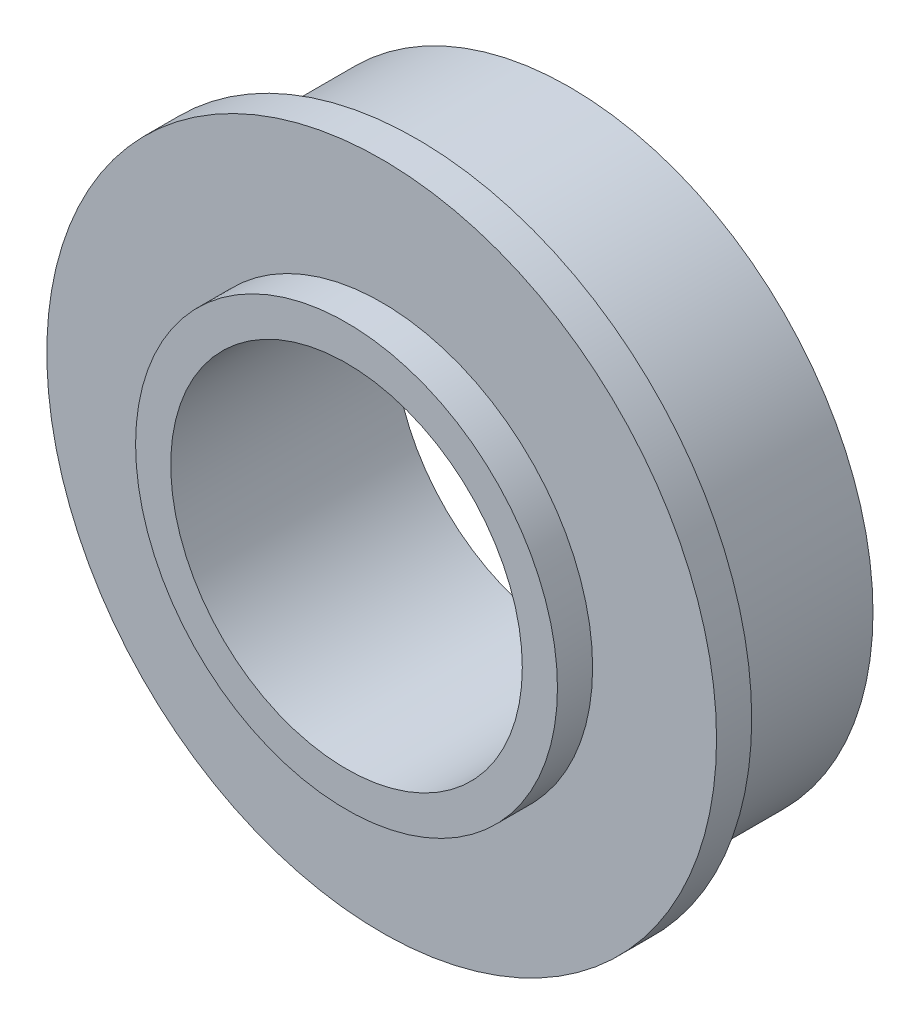
SolidWorks part; units mm, degrees
ref_plane "Front Plane" through (0, 0, 0) normal (0, 0, 1) x (1, 0, 0)
ref_plane "Top Plane" through (0, 0, 0) normal (0, 1, 0) x (1, 0, 0)
ref_plane "Right Plane" through (0, 0, 0) normal (1, 0, 0) x (0, 0, -1)
sketch "Sketch1" plane through (0, 0, 0) normal (0, 0, 1) x (1, 0, 0)
  circle A0 centre (0, 0) radius 10
  circle A1 centre (0, 0) radius 17.25
  dimension "D1" = 20
  dimension "D2" = 34.5
extrude "Boss-Extrude1" add sketch "Sketch1" along normal blind 8.7
sketch "Sketch2" plane through (0, 0, 8.7) normal (0, 0, 1) x (1, 0, 0)
  circle A0 centre (0, 0) radius 19.05
  circle A1 centre (0, 0) radius 10
  circle A2 centre (0, 0) radius 10 construction
  dimension "D1" = 38.1
extrude "Boss-Extrude2" add sketch "Sketch2" along normal blind 2
sketch "Sketch3" plane through (0, 0, 10.7) normal (0, 0, 1) x (1, 0, 0)
  circle A0 centre (0, 0) radius 10
  circle A1 centre (0, 0) radius 12
  circle A2 centre (0, 0) radius 10 construction
  dimension "D1" = 2
extrude "Boss-Extrude3" add sketch "Sketch3" along normal blind 2
